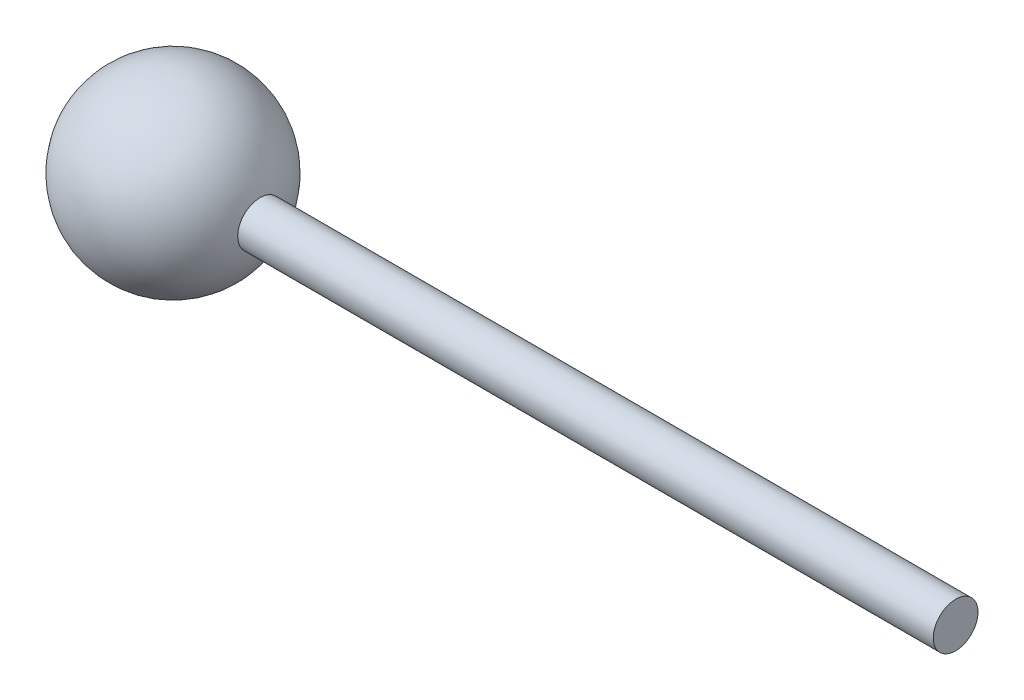
SolidWorks part; units mm, degrees
ref_plane "Front Plane" through (0, 0, 0) normal (0, 0, 1) x (1, 0, 0)
ref_plane "Top Plane" through (0, 0, 0) normal (0, 1, 0) x (1, 0, 0)
ref_plane "Right Plane" through (0, 0, 0) normal (1, 0, 0) x (0, 0, -1)
sketch "Sketch1" plane through (0, 0, 0) normal (1, 0, 0) x (0, 0, -1)
  circle A0 centre (0, 0) radius 1.27
  dimension "D1" = 2.54
extrude "Extrude1" add sketch "Sketch1" along normal mid plane 44.45
sketch "Sketch2" plane through (-22.225, 0, 0) normal (-1, 0, 0) x (0, 0, 1)
  line L0 (0, 8.7627) -> (0, -7.6077) construction
  line L1 (0, -5.1054) -> (0, 5.1054)
  arc A0 (0, 5.1054) -> (0, -5.1054) centre (0, 0) ccw
  dimension "D1" = 10.2108
revolve "Revolve1" add sketch "Sketch2" angle 360 about L0
